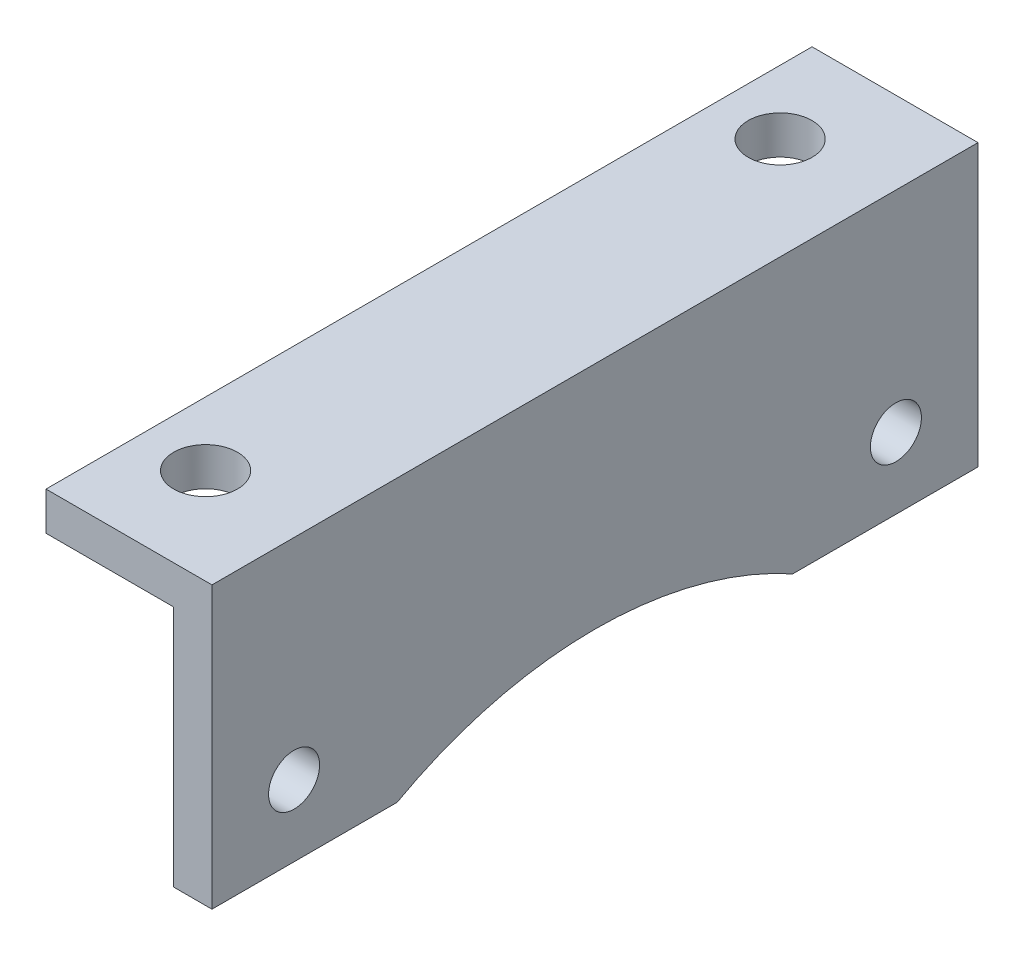
SolidWorks part; units mm, degrees
ref_plane "Alzado" through (0, 0, 0) normal (0, 0, 1) x (1, 0, 0)
ref_plane "Planta" through (0, 0, 0) normal (0, 1, 0) x (1, 0, 0)
ref_plane "Vista lateral" through (0, 0, 0) normal (1, 0, 0) x (0, 0, -1)
sketch "Croquis1" plane through (0, 0, 0) normal (0, 1, 0) x (1, 0, 0)
  line L0 (0, -22.5) -> (0, 22.5) construction
  line L1 (-5, 30) -> (5, 30)
  line L2 (-5, 30) -> (-5, -30)
  line L3 (-5, -30) -> (5, -30)
  line L4 (5, 30) -> (5, -30)
  line L5 (-5, 30) -> (5, -30) construction
  line L6 (-5, -30) -> (5, 30) construction
  circle A0 centre (0, 22.5) radius 2.5
  circle A1 centre (0, -22.5) radius 2.5
  point P0 (0, 0)
  point P9 (0, 0)
  dimension "D4" = 5
  dimension "D1" = 60
  dimension "D2" = 10
  dimension "D3" = 45
extrude "Saliente-Extruir1" add sketch "Croquis1" along normal blind 1.5
fillet "Redondeo1" [suppressed] radius 1
sketch "Croquis2" plane through (0, 1.5, 0) normal (0, 1, 0) x (1, 0, 0)
  line L0 (5, 30) -> (8, 30)
  line L1 (8, 30) -> (8, -30)
  line L2 (8, -30) -> (5, -30)
  line L3 (5, -30) -> (5, 30)
  dimension "D1" = 3
extrude "Saliente-Extruir2" add sketch "Croquis2" against normal blind 12
sketch "Croquis4" plane through (5, 0, 0) normal (-1, 0, 0) x (0, 0, 1)
  line L0 (0, 1.5) -> (0, -78.5) construction
  line L1 (-30, 1.5) -> (30, 1.5) construction
  circle A0 centre (0, -38.5) radius 32
  dimension "D2" = 64
  dimension "D1" = 80
extrude "Cortar-Extruir2" cut sketch "Croquis4" against normal through all
sketch "Sketch1" plane through (0, 0, -30) normal (0, 0, -1) x (-1, 0, 0)
  line L0 (5, 1.5) -> (5, 0) construction
  line L1 (-8, 1.5) -> (5, 1.5)
  line L2 (-8, 1.5) -> (-8, 11.5)
  line L3 (-8, 11.5) -> (5, 11.5)
  line L4 (5, 1.5) -> (5, 11.5)
  dimension "D1" = 10
extrude "Boss-Extrude1" add sketch "Sketch1" against normal up to surface (60 mm away) up to face at (2.6667, -3, 30)
sketch "Sketch2" plane through (0, 0, 0) normal (0, -1, 0) x (1, 0, 0)
  circle A0 centre (0, -22.5) radius 2.5 construction
  circle A1 centre (0, 22.5) radius 2.5 construction
  circle A2 centre (0, -22.5) radius 2.5
  circle A3 centre (0, 22.5) radius 2.5
extrude "Cut-Extrude1" cut sketch "Sketch2" against normal through all
sketch "Sketch3" plane through (0, 0, -30) normal (0, 0, -1) x (-1, 0, 0)
  line L0 (-5, -10.5) -> (-5, 0) construction
  line L1 (5, 0) -> (-5, 0)
  line L2 (5, 0) -> (5, 8.5)
  line L3 (5, 8.5) -> (-5, 8.5)
  line L4 (-5, 0) -> (-5, 8.5)
  line L5 (5, 11.5) -> (-8, 11.5) construction
  dimension "D1" = 3
extrude "Cut-Extrude2" cut sketch "Sketch3" against normal through all
sketch "Sketch4" plane through (5, 0, 0) normal (-1, 0, 0) x (0, 0, 1)
  line L2 (30, 11.5) -> (-30, 11.5) construction
  circle A0 centre (-23.57, -4.93) radius 2
  dimension "D1" = 23.57
  dimension "D2" = 16.43
  dimension "D3" = 4
extrude "Cut-Extrude3" cut sketch "Sketch4" against normal through all
mirror "Mirror1" about plane through (0, 0, 0) normal (0, 0, 1) of "Cut-Extrude3"
